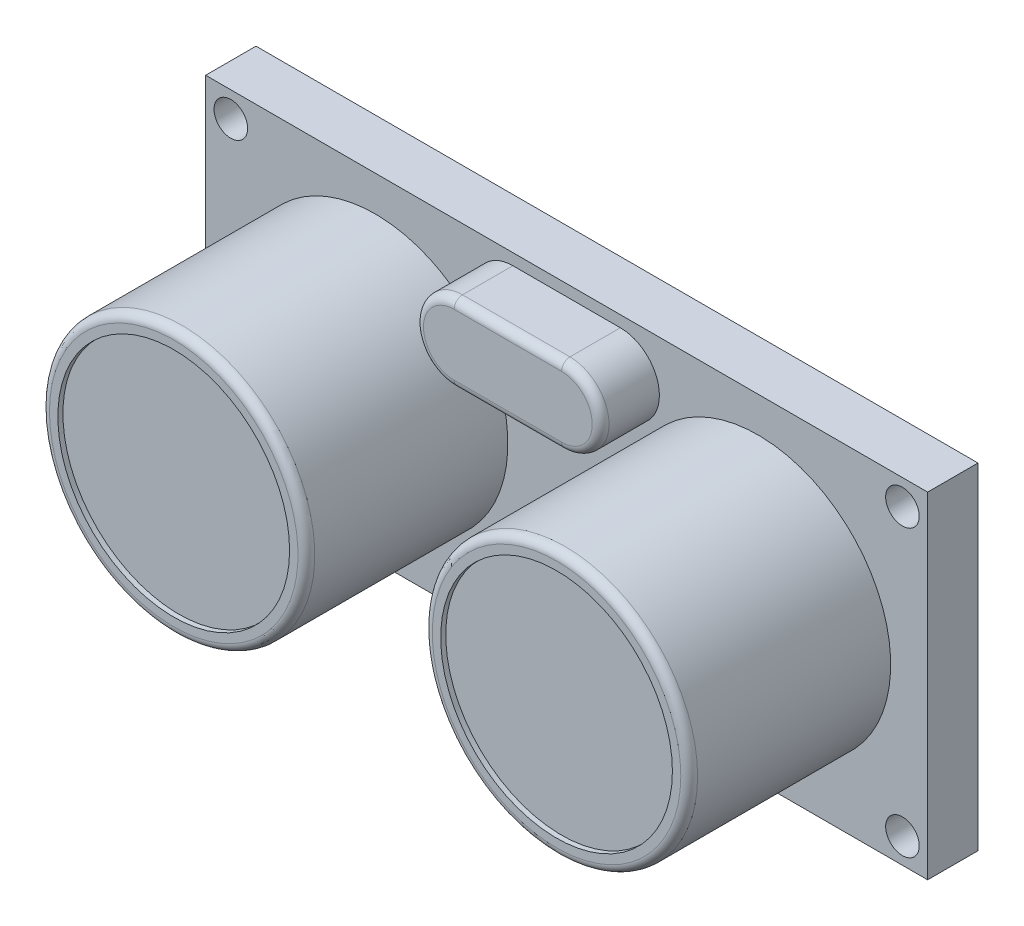
SolidWorks part; units mm, degrees
ref_plane "정면" through (0, 0, 0) normal (0, 0, 1) x (1, 0, 0)
ref_plane "윗면" through (0, 0, 0) normal (0, 1, 0) x (1, 0, 0)
ref_plane "우측면" through (0, 0, 0) normal (1, 0, 0) x (0, 0, -1)
sketch "스케치1" plane through (0, 0, 0) normal (0, 0, 1) x (1, 0, 0)
  line L0 (-63.1454, 0) -> (65.4461, 0) construction
  line L1 (0, -29.8592) -> (0, 43.3803) construction
  line L3 (-21.5, -10) -> (21.5, -10)
  line L4 (-21.5, -10) -> (-21.5, 10)
  line L5 (-21.5, 10) -> (21.5, 10)
  line L10 (21.5, -10) -> (21.5, 10)
  line L11 (-21.5, -10) -> (21.5, 10) construction
  line L12 (-21.5, 10) -> (21.5, -10) construction
  point P5 (0, 0)
other "펜 스케치1" parameters "D1"=33.6899, "D2"=71.1739
extrude "보스-돌출1" add sketch "스케치1" along normal blind 3
sketch "스케치2" plane through (0, 0, 3) normal (0, 0, 1) x (1, 0, 0)
  line L0 (-23.2472, 0) -> (27.9915, 0) construction
  line L1 (0, -15.9929) -> (0, 14.7511) construction
  circle A0 centre (20, 8.5) radius 1
  circle A1 centre (-20, 8.5) radius 1
  circle A2 centre (20, -8.5) radius 1
  circle A3 centre (-20, -8.5) radius 1
  dimension "D2" = 2
  dimension "D1" = 8.5
  dimension "D3" = 40
extrude "컷-돌출1" cut sketch "스케치2" against normal through all both and the other way through all
sketch "스케치3" plane through (0, 0, 3) normal (0, 0, 1) x (1, 0, 0)
  line L0 (-25.8431, 0) -> (26.2704, 0) construction
  line L1 (0, 16.0821) -> (0, -14.7029) construction
  circle A0 centre (11.4, 0) radius 7.9
  circle A1 centre (-11.4, 0) radius 7.9
  dimension "D1" = 15.8
  dimension "D2" = 11.4
extrude "보스-돌출2" add sketch "스케치3" along normal blind 12
fillet "필렛1" radius 0.5 2 edges at (19.3, 0, 15) (-19.3, 0, 15)
sketch "스케치5" plane through (0, 0, 15) normal (0, 0, 1) x (1, 0, 0)
  line L0 (24.41, 0) -> (-26.8306, 0) construction
  line L1 (0, 16.8208) -> (0, -15.7425) construction
  circle A8 centre (-11.4, 0) radius 6.9
  circle A9 centre (-11.4, 0) radius 6.9
  circle A11 centre (11.4, 0) radius 6.9
  circle A12 centre (11.4, 0) radius 6.9
  dimension "D1" = 0.5
  dimension "D2" = 0.5
extrude "컷-돌출2" cut sketch "스케치5" against normal blind 0.3
sketch "스케치6" plane through (0, 0, 3) normal (0, 0, 1) x (1, 0, 0)
  line L0 (-23.5491, 0) -> (25.2743, 0) construction
  line L1 (0, -13.241) -> (0, 14.6212) construction
  line L2 (-3.2, 7) -> (3.2, 7) construction
  line L3 (-3.2, 9.325) -> (3.2, 9.325)
  line L4 (-3.2, 4.675) -> (3.2, 4.675)
  arc A0 (-3.2, 9.325) -> (-3.2, 4.675) centre (-3.2, 7) ccw
  arc A1 (3.2, 4.675) -> (3.2, 9.325) centre (3.2, 7) ccw
  point P7 (0, 7)
  point P12 (5.525, 7)
  point P13 (-5.525, 7)
  dimension "D1" = 4.65
  dimension "D2" = 11.05
  dimension "D3" = 7
extrude "보스-돌출3" add sketch "스케치6" along normal blind 3.5
fillet "필렛2" radius 0.5 4 edges at (0, 9.325, 6.5) (5.525, 7, 6.5) (0, 4.675, 6.5) (-5.525, 7, 6.5)
